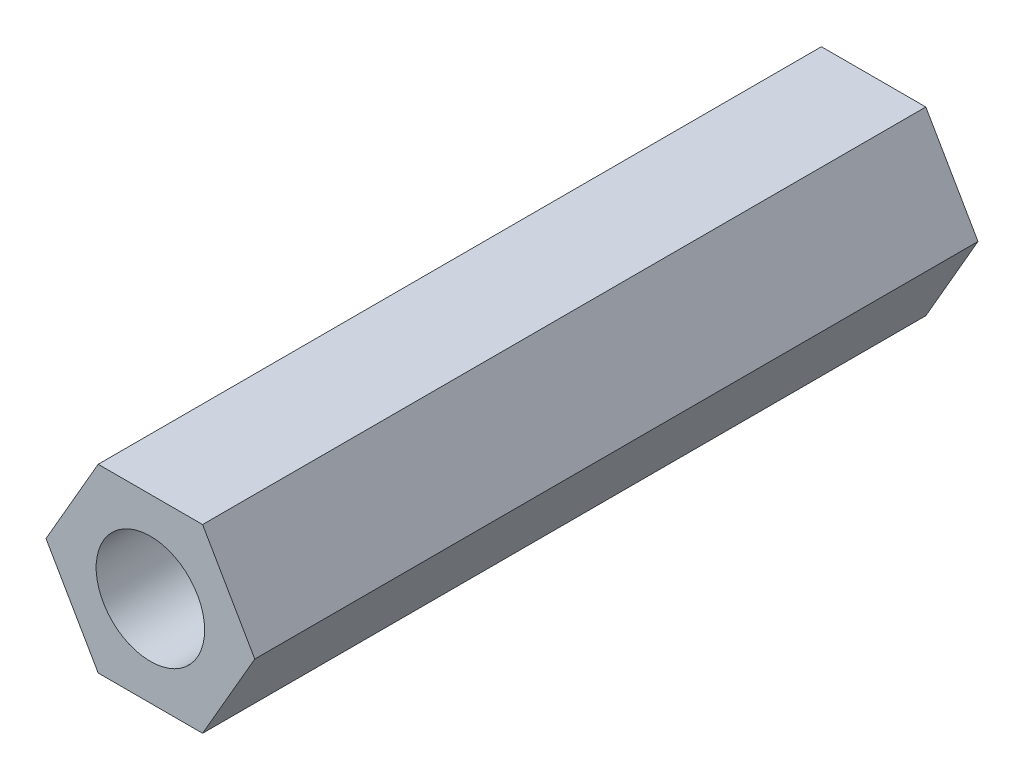
SolidWorks part; units mm, degrees
material "1.4000 (X6Cr13)"
ref_plane "Plan de face" through (0, 0, 0) normal (0, 0, 1) x (1, 0, 0)
ref_plane "Plan de dessus" through (0, 0, 0) normal (0, 1, 0) x (1, 0, 0)
ref_plane "Plan de droite" through (0, 0, 0) normal (1, 0, 0) x (0, 0, -1)
sketch "Esquisse1" plane through (0, 0, 0) normal (0, 0, 1) x (1, 0, 0)
  line L1 (1.4434, 2.5) -> (-1.4434, 2.5)
  line L2 (-1.4434, 2.5) -> (-2.8868, 0)
  line L3 (-2.8868, 0) -> (-1.4434, -2.5)
  line L4 (-1.4434, -2.5) -> (1.4434, -2.5)
  line L5 (1.4434, -2.5) -> (2.8868, 0)
  line L6 (2.8868, 0) -> (1.4434, 2.5)
  circle A0 centre (0, 0) radius 2.5 construction
  circle A1 centre (0, 0) radius 1.5
  dimension "D2" = 3
  dimension "D1" = 5
extrude "Boss.-Extru.1" add sketch "Esquisse1" along normal blind 20
